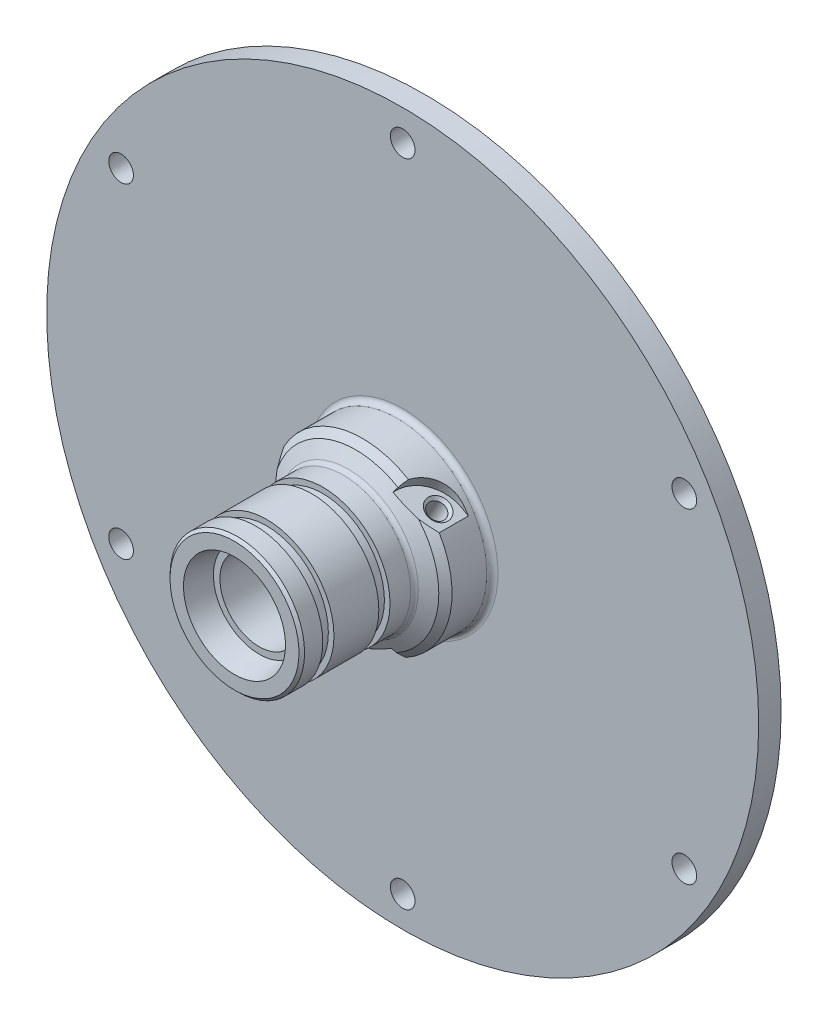
SolidWorks part; units mm, degrees
material "Copper"
ref_plane "Front Plane" through (0, 0, 0) normal (0, 0, 1) x (1, 0, 0)
ref_plane "Top Plane" through (0, 0, 0) normal (0, 1, 0) x (1, 0, 0)
ref_plane "Right Plane" through (0, 0, 0) normal (1, 0, 0) x (0, 0, -1)
ref_axis "CENTER" through (0, 0, 58.5) along (0, 0, -1)
sketch "Sketch2" plane through (0, 0, 0) normal (1, 0, 0) x (0, 0, -1)
  line L0 (0, 0) -> (0, 31.75)
  line L1 (0, 31.75) -> (-2, 31.75)
  line L2 (-2, 31.75) -> (-2, 8)
  line L3 (-2, 8) -> (-7, 8)
  line L4 (-7, 8) -> (-7, 6)
  line L5 (-17, 0) -> (0, 0)
  line L6 (29.1956, 0) -> (45826.297, 0) construction
  line L7 (-7, 6) -> (-17, 6)
  line L8 (-17, 6) -> (-17, 0)
  dimension "D1" = 63.5
  dimension "D2" = 2
  dimension "D3" = 16
  dimension "D4" = 5
  dimension "D5" = 12
  dimension "D6" = 15
revolve "Main Base" add sketch "Sketch2" angle 360 about L6
hole_wizard "Ø6.5 (6.5) Diameter Hole1" positions "Sketch4" profile "Sketch5" hole size "Ø6.5" standard "ANSI Metric" end condition through all
sketch "Sketch4" plane through (0, 0, 17) normal (0, 0, 1) x (1, 0, 0)
  point P0 (0, 0)
sketch "Sketch5" plane through (0, 0, 17) normal (1, 0, 0) x (0, -1, 0)
  line L0 (0, 0) -> (0, 17)
  line L1 (0, 17) -> (3.25, 17)
  line L2 (3.25, 17) -> (3.25, 0)
  line L5 (3.25, 0) -> (0, 0)
  line L11 (0, -6.35) -> (0, 107.95) construction
  dimension "Thru Hole Dia." = 6.5
  dimension "Thru Hole Depth" = 17
hole_wizard "Ø7.0 (7) Diameter Hole1" positions "Sketch12" profile "Sketch13" hole size "Ø7.0" standard "ANSI Metric"
sketch "Sketch12" plane through (0, 0, 17) normal (0, 0, 1) x (1, 0, 0)
  point P0 (0, 0)
sketch "Sketch13" plane through (0, 0, 17) normal (1, 0, 0) x (0, -1, 0)
  line L0 (0, 0) -> (0, 11.103)
  line L1 (0, 11.103) -> (3.5, 9)
  line L2 (3.5, 9) -> (3.5, 0)
  line L5 (3.5, 0) -> (0, 0)
  line L10 (0, 11.103) -> (-3.5, 9) construction
  line L11 (0, -6.35) -> (0, 107.95) construction
  dimension "Hole Dia." = 7
  dimension "Hole Depth" = 9
  dimension "Drill Angle" = 118
cosmetic thread "Cosmetic Thread1" parameters "D2"=10
sketch "Sketch6" plane through (0, 0, 0) normal (1, 0, 0) x (0, 0, -1)
  line L0 (-6.175, 3.25) -> (-7, 3.25) construction
  line L1 (-6.175, 0.075) -> (-7, 0.075)
  line L4 (-3, -5.9353) -> (-3, -50005.9353) construction
  line L5 (-2, 31.75) -> (-2, -31.75) construction
  line L7 (-3, 3.25) -> (-3, 8)
  line L8 (-3, 8) -> (-10.175, 8)
  line L9 (-10.175, 8) -> (-10.175, 3.25)
  line L10 (-7, 8) -> (-7, -8) construction
  arc A0 (-6.175, 0.075) -> (-3, 3.25) centre (-6.175, 3.25) ccw
  arc A1 (-10.175, 3.25) -> (-7, 0.075) centre (-7, 3.25) ccw
  point P2 (-6.5875, 1.1906)
  dimension "D1" = 3.175
  dimension "D2" = 1
  dimension "D3" = 3.25
extrude "Drill Flat" cut sketch "Sketch6" against normal through all from offset 7 offset against normal yes
sketch "Sketch7" plane through (-7, 0, 0) normal (-1, 0, 0) x (0, 0, 1)
  line L1 (7, 3.873) -> (7, 0.075) construction
  line L2 (7.8498, 3.25) -> (0, 3.25) construction
  circle A0 centre (4.5, 2.5) radius 0.75
  dimension "D1" = 1.5
  dimension "D2" = 2.5
extrude "Fuel Inlet" cut sketch "Sketch7" against normal up to next
pattern_circular "Inlets" count 3 over 360 about axis through (0, 0, 0) along (0, 0, 1) of "Fuel Inlet", "Drill Flat"
sketch "Sketch8" plane through (0, 0, 0) normal (1, 0, 0) x (0, 0, -1)
  line L0 (-7, 6) -> (-5.8453, 8)
  line L1 (-2, 8) -> (-7, 8) construction
  line L2 (-5.8453, 8) -> (-7, 8)
  line L3 (-7, 8) -> (-7, 6)
  dimension "D1" = 30
revolve "Cone Cut" cut sketch "Sketch8" angle 360 about axis through (0, 0, 58.5) along (0, 0, -1)
sketch "Sketch10" plane through (0, 0, 0) normal (1, 0, 0) x (0, 0, -1)
  line L0 (-7, 6) -> (-17, 6) construction
  line L1 (-9.1288, 6) -> (-10.1288, 6)
  line L2 (-9.1288, 6) -> (-9.1288, 5.5)
  line L3 (-9.1288, 5.5) -> (-10.1288, 5.5)
  line L4 (-10.1288, 6) -> (-10.1288, 5.5)
  line L6 (-14.1288, 6) -> (-15.1288, 6)
  line L7 (-14.1288, 6) -> (-14.1288, 5.5)
  line L8 (-14.1288, 5.5) -> (-15.1288, 5.5)
  line L9 (-15.1288, 6) -> (-15.1288, 5.5)
  dimension "D1" = 1
  dimension "D4" = 4
  dimension "D5" = 0.5
revolve "Radial O-rings" cut sketch "Sketch10" angle 360 about axis through (0, 0, 58.5) along (0, 0, -1)
sketch "Sketch11" plane through (0, 0, 0) normal (1, 0, 0) x (0, 0, -1)
  line L1 (-17, 4.55) -> (-14.8, 4.0824)
  line L6 (-17.7304, 0) -> (49982.2696, 0) construction
  line L7 (-58.5, 0) -> (51.5, 0) construction
  line L9 (-17, 3.5) -> (-17, 4.55)
  line L11 (-17, 6) -> (-17, -6) construction
  line L12 (-14.8, 4.0824) -> (-14.8, 3.5)
  line L13 (-8, 3.5) -> (-17, 3.5) construction
  line L14 (-14.8, 3.5) -> (-17, 3.5)
  dimension "D1" = 12
  dimension "D2" = 9.1
  dimension "D3" = 2.2
revolve "ORB Port" cut sketch "Sketch11" angle 360 about L6
fillet "Tool Rad" radius 0.5 2 edges at (6, 0, 7) (8, 0, 2)
chamfer "Edge Break" distance 0.25 angle 45 7 edges at (6, 0, 17) (-5.6378, -5.6758, 5.8453) (-2.0965, 7.7204, 5.8453) (7.7343, -2.0446, 5.8453) (5.6651, 4.8122, 5.25) (1.3349, -7.3122, 5.25) (-7, 2.5, 5.25)
sketch "Sketch14" plane through (0, 0, 0) normal (0, 0, 1) x (1, 0, 0)
  line L0 (0, 0) -> (0, 29) construction
  point P4 (0, 29)
  dimension "D1" = 29
hole_wizard "Ø2.2 (2.2) Diameter Hole1" positions "Sketch15" profile "Sketch16" hole size "Ø2.2" standard "ANSI Metric" end condition through all
sketch "Sketch15" plane through (0, 0, 2) normal (0, 0, 1) x (1, 0, 0)
  point P0 (0, 29)
sketch "Sketch16" plane through (0, 29, 2) normal (1, 0, 0) x (0, -1, 0)
  line L0 (0, 0) -> (0, 2)
  line L1 (0, 2) -> (1.1, 2)
  line L2 (1.1, 2) -> (1.1, 0)
  line L5 (1.1, 0) -> (0, 0)
  line L11 (0, -6.35) -> (0, 107.95) construction
  dimension "Thru Hole Dia." = 2.2
  dimension "Thru Hole Depth" = 2
pattern_circular "CirPattern1" count 6 over 360 about axis through (0, 0, 0) along (0, 0, 1) of "Ø2.2 (2.2) Diameter Hole1"
